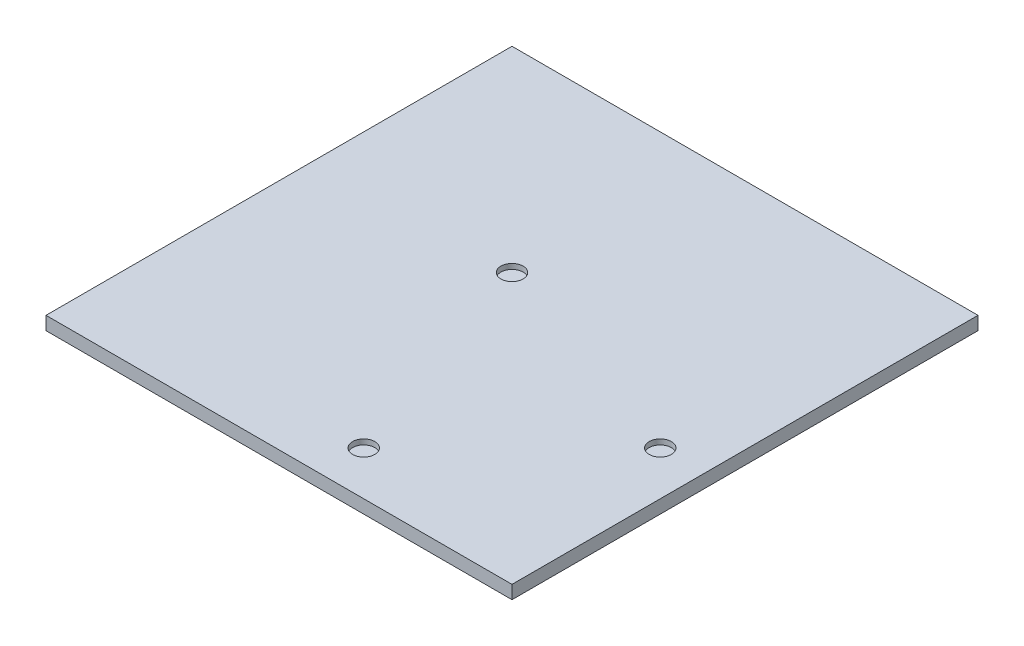
SolidWorks part; units mm, degrees
ref_plane "Front Plane" through (0, 0, 0) normal (0, 0, 1) x (1, 0, 0)
ref_plane "Top Plane" through (0, 0, 0) normal (0, 1, 0) x (1, 0, 0)
ref_plane "Right Plane" through (0, 0, 0) normal (1, 0, 0) x (0, 0, -1)
sketch "Sketch1" plane through (0, 0, 0) normal (0, 1, 0) x (1, 0, 0)
  line L1 (-44.45, -44.45) -> (44.45, -44.45)
  line L2 (-44.45, -44.45) -> (-44.45, 44.45)
  line L3 (-44.45, 44.45) -> (44.45, 44.45)
  line L4 (44.45, -44.45) -> (44.45, 44.45)
  line L5 (-44.45, -44.45) -> (44.45, 44.45) construction
  line L6 (-44.45, 44.45) -> (44.45, -44.45) construction
  point P0 (0, 0)
  dimension "D1" = 88.9
  dimension "D2" = 88.9
extrude "Boss-Extrude1" add sketch "Sketch1" along normal blind 2.54
sketch "Sketch2" plane through (0, 2.54, 0) normal (0, 1, 0) x (1, 0, 0)
  line L0 (0, 44.45) -> (0, -44.45) construction
  line L1 (0, -3.3588) -> (3.3588, 0)
  line L2 (0, -3.3588) -> (-3.3588, 0)
  line L3 (-3.3588, 0) -> (0, 3.3588)
  line L4 (3.3588, 0) -> (0, 3.3588)
  line L5 (0, -3.3588) -> (0, 3.3588) construction
  line L6 (-3.3588, 0) -> (3.3588, 0) construction
  line L7 (44.45, 44.45) -> (-44.45, 44.45) construction
  line L8 (-44.45, -44.45) -> (44.45, -44.45) construction
  point P0 (0, 0)
  dimension "D1" = 4.75
extrude "Boss-Extrude2" [suppressed] add sketch "Sketch2" along normal blind 5
sketch "Sketch3" plane through (0, 2.54, 0) normal (0, 1, 0) x (1, 0, 0)
  line L0 (-44.45, 44.45) -> (44.45, -44.45) construction
  line L1 (44.45, 44.45) -> (-44.45, -44.45) construction
  line L2 (36.0624, -7.7782) -> (7.7782, -36.0624)
  line L4 (0, 0) -> (-7.0711, 7.0711)
  circle A0 centre (-7.0711, 7.0711) radius 2.125
  circle A1 centre (36.0624, -7.7782) radius 2.125
  circle A2 centre (7.7782, -36.0624) radius 2.125
  dimension "D2" = 20
  dimension "D4" = 4.25
  dimension "D1" = 31
  dimension "D3" = 10
  dimension "D5" = 20
extrude "Cut-Extrude1" cut sketch "Sketch3" against normal blind 1
